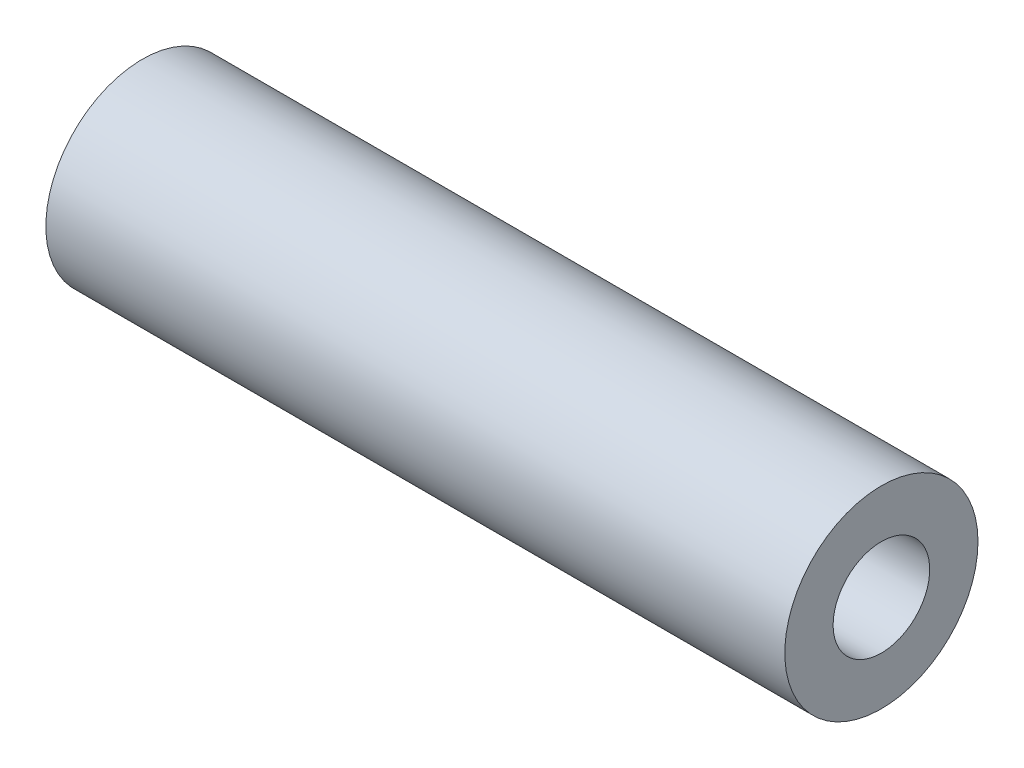
SolidWorks part; units mm, degrees
material "1.4511 (X3CrNb17)"
ref_plane "前视基准面" through (0, 0, 0) normal (0, 0, 1) x (1, 0, 0)
ref_plane "上视基准面" through (0, 0, 0) normal (0, 1, 0) x (1, 0, 0)
ref_plane "右视基准面" through (0, 0, 0) normal (1, 0, 0) x (0, 0, -1)
sketch "草图1" plane through (0, 0, 0) normal (1, 0, 0) x (0, 0, -1)
  circle A0 centre (0, 0) radius 5
  dimension "D1" = 10
extrude "凸台-拉伸1" add sketch "草图1" along normal blind 38.25
hole_wizard "M6 螺纹孔1" positions "草图2" profile "草图3" tap size "M6" standard "GB" end condition through all
sketch "草图2" plane through (0, 0, 0) normal (-1, 0, 0) x (0, 0, 1)
  point P0 (0, 0)
sketch "草图3" plane through (0, 0, 0) normal (0, 1, 0) x (0, 0, 1)
  line L0 (0, 0) -> (0, 38.25)
  line L1 (0, 38.25) -> (2.5, 38.25)
  line L2 (2.5, 38.25) -> (2.5, 0)
  line L5 (2.5, 0) -> (0, 0)
  line L11 (0, -6.35) -> (0, 107.95) construction
  dimension "通孔螺纹孔钻头直径" = 5
  dimension "通孔螺纹孔钻头深度" = 38.25
cosmetic thread "孔螺蚊线1" parameters "D2"=6
